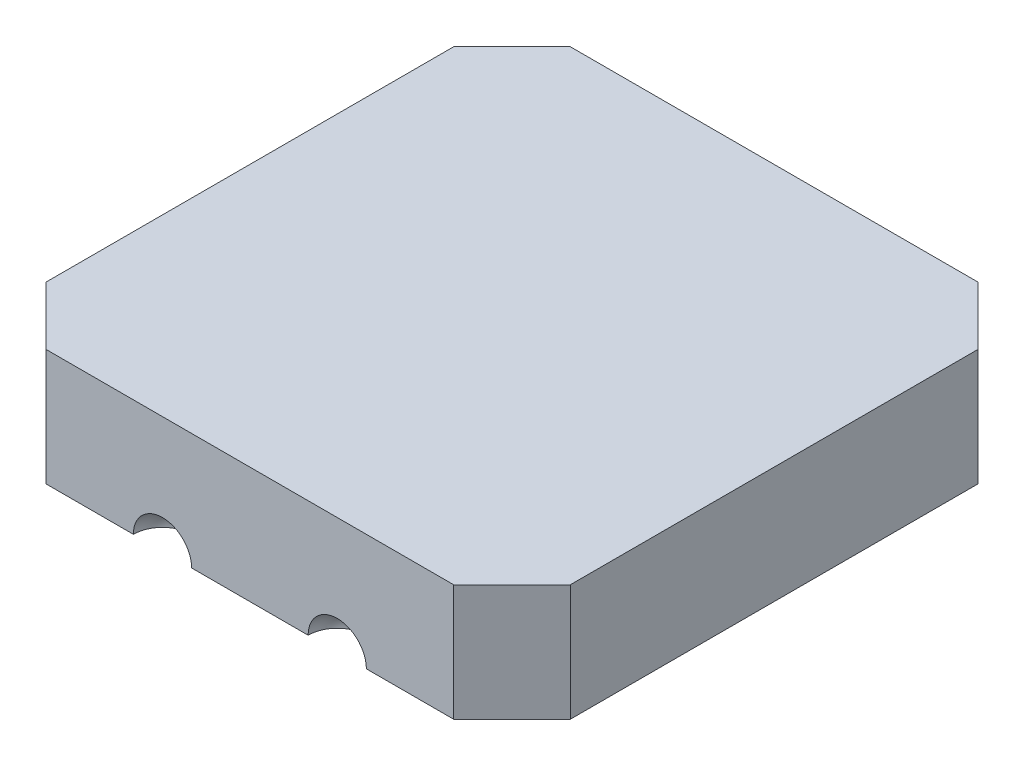
SolidWorks part; units mm, degrees
material "Polyurethane Foam Rigid"
ref_plane "Front Plane" through (0, 0, 0) normal (0, 0, 1) x (1, 0, 0)
ref_plane "Top Plane" through (0, 0, 0) normal (0, 1, 0) x (1, 0, 0)
ref_plane "Right Plane" through (0, 0, 0) normal (1, 0, 0) x (0, 0, -1)
sketch "Sketch1" plane through (0, 0, 0) normal (0, 1, 0) x (1, 0, 0)
  line L1 (-57.15, -57.15) -> (57.15, -57.15)
  line L2 (-57.15, -57.15) -> (-57.15, 57.15)
  line L3 (-57.15, 57.15) -> (57.15, 57.15)
  line L4 (57.15, -57.15) -> (57.15, 57.15)
  line L5 (-57.15, -57.15) -> (57.15, 57.15) construction
  line L6 (-57.15, 57.15) -> (57.15, -57.15) construction
  point P0 (0, 0)
  dimension "D1" = 114.3
  dimension "D2" = 114.3
extrude "Boss-Extrude1" add sketch "Sketch1" along normal blind 25.4
chamfer "Chamfer1" distance 12.7 angle 45 4 edges at (-57.15, 12.7, 57.15) (-57.15, 12.7, -57.15) (57.15, 12.7, -57.15) (57.15, 12.7, 57.15)
sketch "Sketch2" plane through (0, 0, 0) normal (0, -1, 0) x (-1, 0, 0)
  line L0 (44.45, -57.15) -> (-44.45, -57.15) construction
  circle A0 centre (0, -47.625) radius 6.35
  dimension "D2" = 12.7
  dimension "D1" = 9.525
extrude "Cut-Extrude1" cut sketch "Sketch2" against normal blind 5.08 contours A0
sketch "Sketch3" plane through (0, 0, 57.15) normal (0, 0, 1) x (1, 0, 0)
  line L0 (-44.45, 0) -> (44.45, 0) construction
  line L1 (-44.45, 25.4) -> (-44.45, 0) construction
  line L2 (-25.4, 0) -> (-12.7, 0)
  line L3 (0, -13.97) -> (0, 13.97) construction
  line L4 (25.4, 0) -> (12.7, 0)
  arc A0 (-12.7, 0) -> (-25.4, 0) centre (-19.05, 0) ccw
  arc A1 (12.7, 0) -> (25.4, 0) centre (19.05, 0) cw
  dimension "D1" = 6.35
  dimension "D2" = 25.4
revolve "Cut-Revolve4" cut sketch "Sketch3" angle 360 about axis through (-57.15, 0, 57.15) along (1, 0, 0)
